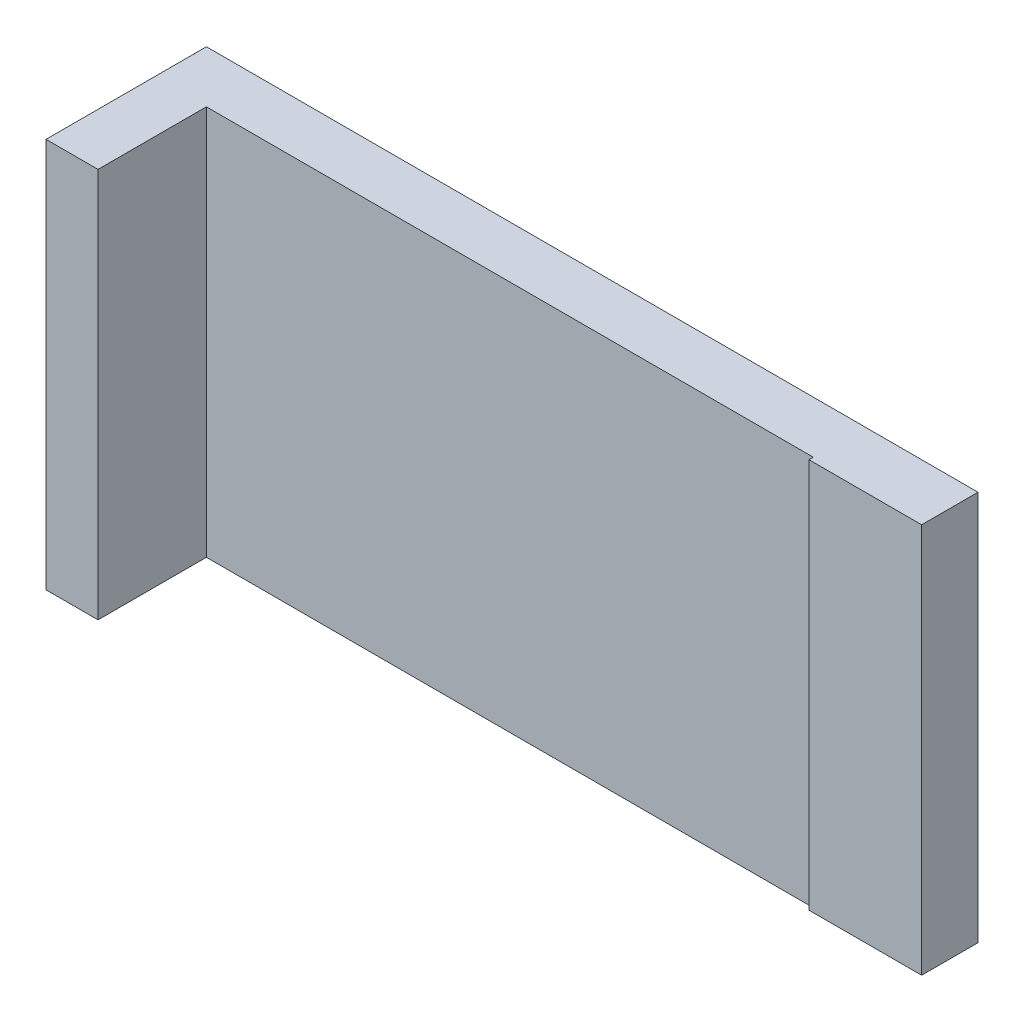
SolidWorks part; units mm, degrees
ref_plane "Plano frontal" through (0, 0, 0) normal (0, 0, 1) x (1, 0, 0)
ref_plane "Plano superior" through (0, 0, 0) normal (0, 1, 0) x (1, 0, 0)
ref_plane "Plano direito" through (0, 0, 0) normal (1, 0, 0) x (0, 0, -1)
sketch "Esboço1" plane through (0, 0, 0) normal (0, 0, 1) x (1, 0, 0)
  line L0 (-16, 3.25) -> (-16, -3.25) construction
  line L1 (-16.25, -11.25) -> (25.25, -11.25)
  line L2 (-16.25, -11.25) -> (-16.25, 11.25)
  line L3 (-16.25, 11.25) -> (25.25, 11.25)
  line L4 (25.25, -11.25) -> (25.25, 11.25)
  line L6 (22, -8) -> (22, -11.25) construction
  line L7 (22, -8) -> (25.25, -8) construction
  line L9 (22, 8) -> (22, 11.25) construction
  line L11 (25.5, -8.2779) -> (25.5, 29.7721) construction
  dimension "D1" = 0.25
  dimension "D2" = 0.25
extrude "Ressalto-extrusão1" add sketch "Esboço1" against normal blind 3
sketch "Esboço2" plane through (-16.25, 0, 0) normal (-1, 0, 0) x (0, 0, 1)
  line L1 (-3, -11.25) -> (6.25, -11.25)
  line L2 (-3, -11.25) -> (-3, 11.25)
  line L3 (-3, 11.25) -> (6.25, 11.25)
  line L4 (6.25, -11.25) -> (6.25, 11.25)
  line L5 (6.5, 29.8) -> (6.5, 13.8) construction
  line L6 (-3, 11.25) -> (0, 11.25) construction
  dimension "D1" = 0.25
extrude "Ressalto-extrusão2" add sketch "Esboço2" along normal blind 3
sketch "Esboço3" plane through (0, 0, -3) normal (0, 0, 1) x (1, 0, 0)
  line L0 (25.25, 11.25) -> (-16.25, 11.25) construction
  line L1 (25.25, -11.25) -> (18.75, -11.25)
  line L2 (25.25, -11.25) -> (25.25, 11.25)
  line L3 (25.25, 11.25) -> (18.75, 11.25)
  line L4 (18.75, -11.25) -> (18.75, 11.25)
  line L5 (18.75, 16) -> (25.25, 16) construction
  circle A0 centre (22, 16) radius 1.25 construction
  point P9 (22, 16)
extrude "Ressalto-extrusão3" add sketch "Esboço3" along normal offset from surface (3.25 mm away) 0.25
move or copy body "Corpo-Mover/Copiar1" [suppressed] bodies to move or copy 102 103
